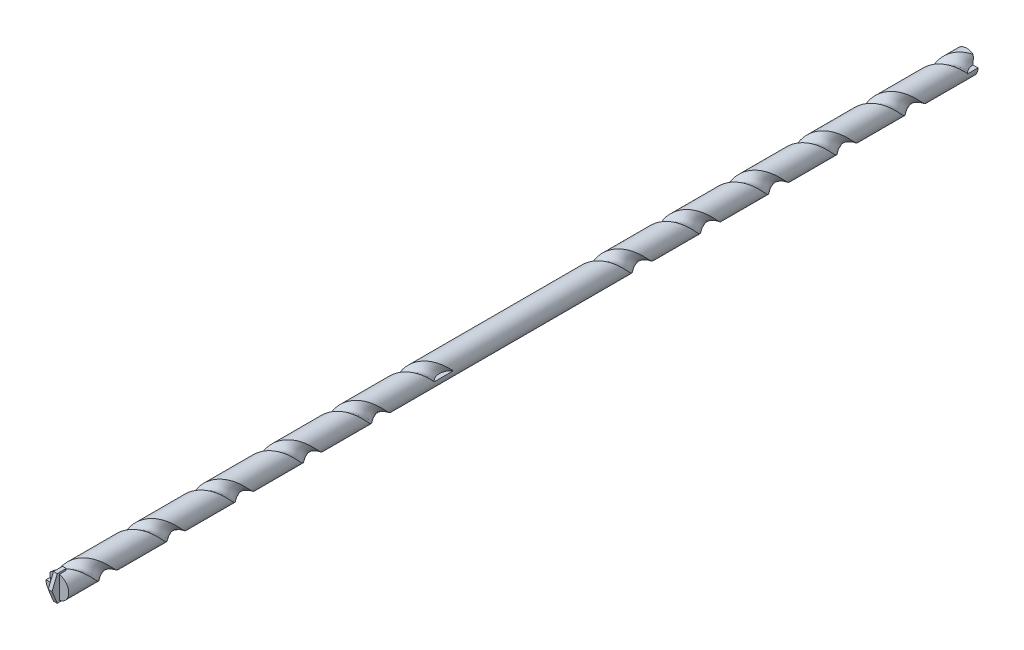
SolidWorks part; units mm, degrees
ref_plane "Front Plane" through (0, 0, 0) normal (0, 0, 1) x (1, 0, 0)
ref_plane "Top Plane" through (0, 0, 0) normal (0, 1, 0) x (1, 0, 0)
ref_plane "Right Plane" through (0, 0, 0) normal (1, 0, 0) x (0, 0, -1)
sketch "Sketch1" plane through (0, 0, 0) normal (0, 0, 1) x (1, 0, 0)
  circle A0 centre (0, 0) radius 30
extrude "Boss-Extrude1" add sketch "Sketch1" along normal blind 1200
sketch "Sketch2" plane through (0, 0, 1200) normal (0, 0, 1) x (1, 0, 0)
  circle A0 centre (0, 0) radius 50
curve "Helix/Spiral1" pitch 180 height 990 turns 5.5
sketch "Sketch3" plane through (0, 0, 0) normal (1, 0, 0) x (0, 0, -1)
  circle A0 centre (-795.098, 49.9996) radius 32
  spline S0 degree 3 poles (-1200, 0) (-1198.2182, 3.1099) (-1194.6477, 9.3414) (-1189.2975, 18.3542) (-1183.9459, 26.731) (-1178.5946, 34.1771) (-1173.2432, 40.4343) (-1167.8919, 45.2847) (-1162.5405, 48.5595) (-1157.1892, 50.1449) (-1151.8378, 49.9856) (-1146.4865, 48.0872) (-1141.1351, 44.5157) (-1135.7838, 39.3955) (-1130.4324, 32.9047) (-1125.0811, 25.269) (-1119.7297, 16.7541) (-1114.3784, 7.6564) (-1109.027, -1.7077) (-1103.6757, -11.0124) (-1098.3243, -19.934) (-1092.973, -28.162) (-1087.6216, -35.4103) (-1082.2703, -41.4265) (-1076.9189, -46.0014) (-1071.5676, -48.9758) (-1066.2162, -50.2463) (-1060.8649, -49.7686) (-1055.5135, -47.5594) (-1050.1622, -43.6955) (-1044.8108, -38.3113) (-1039.4595, -31.5942) (-1034.1081, -23.7779) (-1028.7568, -15.1343) (-1023.4054, -5.9642) (-1018.0541, 3.4135) (-1012.7027, 12.6724) (-1007.3514, 21.4904) (-1002, 29.5607) (-996.6486, 36.6025) (-991.2973, 42.3709) (-985.9459, 46.665) (-980.5946, 49.3357) (-975.2432, 50.2898) (-969.8919, 49.4943) (-964.5405, 46.9767) (-959.1892, 42.8248) (-953.8378, 37.1829) (-948.4865, 30.2473) (-943.1351, 22.2594) (-937.7838, 13.497) (-932.4324, 4.265) (-927.0811, -5.1153) (-921.7297, -14.3177) (-916.3784, -23.0219) (-911.027, -30.9252) (-905.6757, -37.7525) (-900.3243, -43.2664) (-894.973, -47.2749) (-889.6216, -49.6386) (-884.2703, -50.2753) (-878.9189, -49.1628) (-873.5676, -46.3399) (-868.2162, -41.9047) (-862.8649, -36.0116) (-857.5135, -28.8655) (-852.1622, -20.7152) (-846.8108, -11.8441) (-841.4595, -2.561) (-836.1081, 6.8113) (-830.7568, 15.9465) (-825.4054, 24.527) (-820.0541, 32.2541) (-814.7027, 38.859) (-809.3514, 44.112) (-804, 47.8302) (-798.6486, 49.8843) (-793.2973, 50.2028) (-787.9459, 48.7747) (-782.5946, 45.6496) (-777.2432, 40.9363) (-771.8919, 34.7987) (-766.5405, 27.4504) (-761.1892, 19.1471) (-755.8378, 10.1776) (-750.4865, 0.854) (-745.1351, -8.4993) (-739.7838, -17.5569) (-734.4324, -26.0037) (-729.0811, -33.5458) (-723.7297, -39.9207) (-718.3784, -44.9067) (-713.027, -48.3303) (-707.6757, -50.0724) (-702.3243, -50.0724) (-696.973, -48.3303) (-691.6216, -44.9067) (-686.2703, -39.9207) (-680.9189, -33.5458) (-675.5676, -26.0037) (-670.2162, -17.5569) (-664.8649, -8.4993) (-659.5135, 0.854) (-654.1622, 10.1776) (-648.8108, 19.1471) (-643.4595, 27.4504) (-638.1081, 34.7987) (-632.7568, 40.9363) (-627.4054, 45.6496) (-622.0541, 48.7747) (-616.7027, 50.2028) (-611.3514, 49.8843) (-606, 47.8302) (-600.6486, 44.112) (-595.2973, 38.859) (-589.9459, 32.2541) (-584.5946, 24.527) (-579.2432, 15.9465) (-573.8919, 6.8113) (-568.5405, -2.561) (-563.1892, -11.8441) (-557.8378, -20.7152) (-552.4865, -28.8655) (-547.1351, -36.0116) (-541.7838, -41.9047) (-536.4324, -46.3399) (-531.0811, -49.1628) (-525.7297, -50.2753) (-520.3784, -49.6386) (-515.027, -47.2749) (-509.6757, -43.2664) (-504.3243, -37.7525) (-498.973, -30.9252) (-493.6216, -23.0219) (-488.2703, -14.3177) (-482.9189, -5.1153) (-477.5676, 4.265) (-472.2162, 13.497) (-466.8649, 22.2594) (-461.5135, 30.2473) (-456.1622, 37.1829) (-450.8108, 42.8248) (-445.4595, 46.9767) (-440.1081, 49.4943) (-434.7568, 50.2898) (-429.4054, 49.3357) (-424.0541, 46.665) (-418.7027, 42.3709) (-413.3514, 36.6025) (-408, 29.5607) (-402.6486, 21.4904) (-397.2973, 12.6724) (-391.9459, 3.4135) (-386.5946, -5.9642) (-381.2432, -15.1343) (-375.8919, -23.7779) (-370.5405, -31.5942) (-365.1892, -38.3113) (-359.8378, -43.6955) (-354.4865, -47.5594) (-349.1351, -49.7686) (-343.7838, -50.2463) (-338.4324, -48.9758) (-333.0811, -46.0014) (-327.7297, -41.4265) (-322.3784, -35.4103) (-317.027, -28.162) (-311.6757, -19.934) (-306.3243, -11.0124) (-300.973, -1.7077) (-295.6216, 7.6564) (-290.2703, 16.7541) (-284.9189, 25.269) (-279.5676, 32.9047) (-274.2162, 39.3955) (-268.8649, 44.5157) (-263.5135, 48.0872) (-258.1622, 49.9856) (-252.8108, 50.1449) (-247.4595, 48.5595) (-242.1081, 45.2847) (-236.7568, 40.4343) (-231.4054, 34.1771) (-226.0541, 26.731) (-220.7025, 18.3542) (-215.3523, 9.3414) (-211.7818, 3.1099) (-210, 0) knots 0 0 0 0 0.005405 0.010811 0.016216 0.021622 0.027027 0.032432 0.037838 0.043243 0.048649 0.054054 0.059459 0.064865 0.07027 0.075676 0.081081 0.086486 0.091892 0.097297 0.102703 0.108108 0.113514 0.118919 0.124324 0.12973 0.135135 0.140541 0.145946 0.151351 0.156757 0.162162 0.167568 0.172973 0.178378 0.183784 0.189189 0.194595 0.2 0.205405 0.210811 0.216216 0.221622 0.227027 0.232432 0.237838 0.243243 0.248649 0.254054 0.259459 0.264865 0.27027 0.275676 0.281081 0.286486 0.291892 0.297297 0.302703 0.308108 0.313514 0.318919 0.324324 0.32973 0.335135 0.340541 0.345946 0.351351 0.356757 0.362162 0.367568 0.372973 0.378378 0.383784 0.389189 0.394595 0.4 0.405405 0.410811 0.416216 0.421622 0.427027 0.432432 0.437838 0.443243 0.448649 0.454054 0.459459 0.464865 0.47027 0.475676 0.481081 0.486486 0.491892 0.497297 0.502703 0.508108 0.513514 0.518919 0.524324 0.52973 0.535135 0.540541 0.545946 0.551351 0.556757 0.562162 0.567568 0.572973 0.578378 0.583784 0.589189 0.594595 0.6 0.605405 0.610811 0.616216 0.621622 0.627027 0.632432 0.637838 0.643243 0.648649 0.654054 0.659459 0.664865 0.67027 0.675676 0.681081 0.686486 0.691892 0.697297 0.702703 0.708108 0.713514 0.718919 0.724324 0.72973 0.735135 0.740541 0.745946 0.751351 0.756757 0.762162 0.767568 0.772973 0.778378 0.783784 0.789189 0.794595 0.8 0.805405 0.810811 0.816216 0.821622 0.827027 0.832432 0.837838 0.843243 0.848649 0.854054 0.859459 0.864865 0.87027 0.875676 0.881081 0.886486 0.891892 0.897297 0.902703 0.908108 0.913514 0.918919 0.924324 0.92973 0.935135 0.940541 0.945946 0.951351 0.956757 0.962162 0.967568 0.972973 0.978378 0.983784 0.989189 0.994595 1 1 1 1 construction
sweep "Cut-Sweep1" cut profiles "Sketch3" path "Helix/Spiral1"
sketch "Sketch4" plane through (0, 0, 0) normal (0, 0, -1) x (-1, 0, 0)
  circle A0 centre (0, 0) radius 30
extrude "Boss-Extrude2" add sketch "Sketch4" along normal blind 1200
sketch "Sketch5" plane through (0, 0, -1200) normal (0, 0, -1) x (-1, 0, 0)
  circle A0 centre (0, 0) radius 51.5555
curve "Helix/Spiral2" pitch 180 height 990 turns 5.5
sketch "Sketch6" plane through (0, 0, 0) normal (1, 0, 0) x (0, 0, -1)
  circle A0 centre (795.1665, 51.5545) radius 34.7212
  spline S0 degree 3 poles (1200, 0) (1198.2372, 3.1724) (1194.705, 9.529) (1189.412, 18.7299) (1184.1176, 27.2955) (1178.8235, 34.9309) (1173.5294, 41.377) (1168.2353, 46.414) (1162.9412, 49.8704) (1157.6471, 51.6286) (1152.3529, 51.6286) (1147.0588, 49.8704) (1141.7647, 46.414) (1136.4706, 41.377) (1131.1765, 34.931) (1125.8824, 27.2954) (1120.5882, 18.7303) (1113.5294, 6.4597) (1106.4706, -6.4597) (1099.4118, -18.7303) (1094.1176, -27.2954) (1088.8235, -34.931) (1083.5294, -41.377) (1078.2353, -46.414) (1072.9412, -49.8704) (1067.6471, -51.6286) (1062.3529, -51.6286) (1057.0588, -49.8704) (1051.7647, -46.414) (1046.4706, -41.377) (1041.1765, -34.931) (1035.8824, -27.2954) (1030.5882, -18.7303) (1023.5294, -6.4597) (1016.4706, 6.4597) (1009.4118, 18.7303) (1004.1176, 27.2954) (998.8235, 34.931) (993.5294, 41.377) (988.2353, 46.414) (982.9412, 49.8704) (977.6471, 51.6286) (972.3529, 51.6286) (967.0588, 49.8704) (961.7647, 46.414) (956.4706, 41.377) (951.1765, 34.931) (945.8824, 27.2954) (940.5882, 18.7303) (933.5294, 6.4597) (926.4706, -6.4597) (919.4118, -18.7303) (914.1176, -27.2954) (908.8235, -34.931) (903.5294, -41.377) (898.2353, -46.414) (892.9412, -49.8704) (887.6471, -51.6286) (882.3529, -51.6286) (877.0588, -49.8704) (871.7647, -46.414) (866.4706, -41.377) (861.1765, -34.931) (855.8824, -27.2954) (850.5882, -18.7303) (843.5294, -6.4597) (836.4706, 6.4597) (829.4118, 18.7303) (824.1176, 27.2954) (818.8235, 34.931) (813.5294, 41.377) (808.2353, 46.414) (802.9412, 49.8704) (797.6471, 51.6286) (792.3529, 51.6286) (787.0588, 49.8704) (781.7647, 46.414) (776.4706, 41.377) (771.1765, 34.931) (765.8824, 27.2954) (760.5882, 18.7303) (753.5294, 6.4597) (746.4706, -6.4597) (739.4118, -18.7303) (734.1176, -27.2954) (728.8235, -34.931) (723.5294, -41.377) (718.2353, -46.414) (712.9412, -49.8704) (707.6471, -51.6286) (702.3529, -51.6286) (697.0588, -49.8704) (691.7647, -46.414) (686.4706, -41.377) (681.1765, -34.931) (675.8824, -27.2954) (670.5882, -18.7303) (663.5294, -6.4597) (656.4706, 6.4597) (649.4118, 18.7303) (644.1176, 27.2954) (638.8235, 34.931) (633.5294, 41.377) (628.2353, 46.414) (622.9412, 49.8704) (617.6471, 51.6286) (612.3529, 51.6286) (607.0588, 49.8704) (601.7647, 46.414) (596.4706, 41.377) (591.1765, 34.931) (585.8824, 27.2954) (580.5882, 18.7303) (573.5294, 6.4597) (566.4706, -6.4597) (559.4118, -18.7303) (554.1176, -27.2954) (548.8235, -34.931) (543.5294, -41.377) (538.2353, -46.414) (532.9412, -49.8704) (527.6471, -51.6286) (522.3529, -51.6286) (517.0588, -49.8704) (511.7647, -46.414) (506.4706, -41.377) (501.1765, -34.931) (495.8824, -27.2954) (490.5882, -18.7303) (483.5294, -6.4597) (476.4706, 6.4597) (469.4118, 18.7303) (464.1176, 27.2954) (458.8235, 34.931) (453.5294, 41.377) (448.2353, 46.414) (442.9412, 49.8704) (437.6471, 51.6286) (432.3529, 51.6286) (427.0588, 49.8704) (421.7647, 46.414) (416.4706, 41.377) (411.1765, 34.931) (405.8824, 27.2954) (400.5882, 18.7303) (393.5294, 6.4597) (386.4706, -6.4597) (379.4118, -18.7303) (374.1176, -27.2954) (368.8235, -34.931) (363.5294, -41.377) (358.2353, -46.414) (352.9412, -49.8704) (347.6471, -51.6286) (342.3529, -51.6286) (337.0588, -49.8704) (331.7647, -46.414) (326.4706, -41.377) (321.1765, -34.931) (315.8824, -27.2954) (310.5882, -18.7303) (303.5294, -6.4597) (296.4706, 6.4597) (289.4118, 18.7303) (284.1176, 27.2954) (278.8235, 34.931) (273.5294, 41.377) (268.2353, 46.414) (262.9412, 49.8704) (257.6471, 51.6286) (252.3529, 51.6286) (247.0588, 49.8704) (241.7647, 46.414) (236.4706, 41.377) (231.1765, 34.9309) (225.8824, 27.2955) (220.588, 18.7299) (215.295, 9.529) (211.7628, 3.1724) (210, 0) knots 0 0 0 0 0.005348 0.010695 0.016043 0.02139 0.026738 0.032086 0.037433 0.042781 0.048128 0.053476 0.058824 0.064171 0.069519 0.074866 0.080214 0.085561 0.096257 0.101604 0.106952 0.112299 0.117647 0.122995 0.128342 0.13369 0.139037 0.144385 0.149733 0.15508 0.160428 0.165775 0.171123 0.176471 0.187166 0.192513 0.197861 0.203209 0.208556 0.213904 0.219251 0.224599 0.229947 0.235294 0.240642 0.245989 0.251337 0.256684 0.262032 0.26738 0.278075 0.283422 0.28877 0.294118 0.299465 0.304813 0.31016 0.315508 0.320856 0.326203 0.331551 0.336898 0.342246 0.347594 0.352941 0.358289 0.368984 0.374332 0.379679 0.385027 0.390374 0.395722 0.40107 0.406417 0.411765 0.417112 0.42246 0.427807 0.433155 0.438503 0.44385 0.449198 0.459893 0.465241 0.470588 0.475936 0.481283 0.486631 0.491979 0.497326 0.502674 0.508021 0.513369 0.518717 0.524064 0.529412 0.534759 0.540107 0.550802 0.55615 0.561497 0.566845 0.572193 0.57754 0.582888 0.588235 0.593583 0.59893 0.604278 0.609626 0.614973 0.620321 0.625668 0.631016 0.641711 0.647059 0.652406 0.657754 0.663102 0.668449 0.673797 0.679144 0.684492 0.68984 0.695187 0.700535 0.705882 0.71123 0.716578 0.721925 0.73262 0.737968 0.743316 0.748663 0.754011 0.759358 0.764706 0.770053 0.775401 0.780749 0.786096 0.791444 0.796791 0.802139 0.807487 0.812834 0.823529 0.828877 0.834225 0.839572 0.84492 0.850267 0.855615 0.860963 0.86631 0.871658 0.877005 0.882353 0.887701 0.893048 0.898396 0.903743 0.914439 0.919786 0.925134 0.930481 0.935829 0.941176 0.946524 0.951872 0.957219 0.962567 0.967914 0.973262 0.97861 0.983957 0.989305 0.994652 1 1 1 1 construction
sweep "Cut-Sweep2" cut profiles "Sketch6" path "Helix/Spiral2"
sketch "Sketch7" plane through (0, 0, 0) normal (1, 0, 0) x (0, 0, -1)
  line L0 (-1181.5689, 0) -> (-1338.6551, 0) construction
  line L1 (-1181.5689, -33.9617) -> (-1181.5689, 33.9617)
  line L2 (-1181.5689, 33.9617) -> (-1205.3495, 33.9617)
  line L3 (-1205.3495, 33.9617) -> (-1219.082, 0)
  line L4 (-1205.3495, -33.9617) -> (-1219.082, 0)
  line L5 (-1181.5689, -33.9617) -> (-1205.3495, -33.9617)
extrude "Boss-Extrude3" add sketch "Sketch7" along normal mid plane 10
